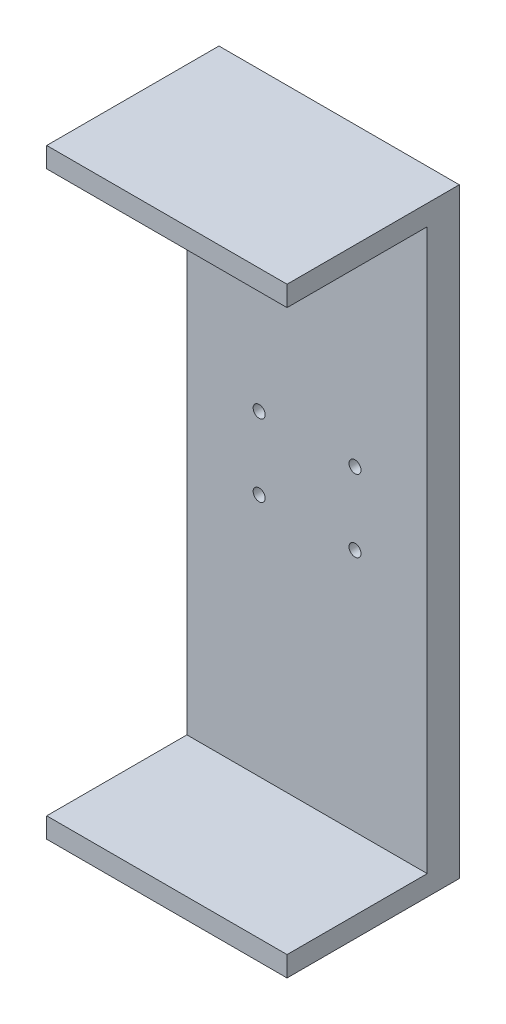
SolidWorks part; units mm, degrees
ref_plane "Front Plane" through (0, 0, 0) normal (0, 0, 1) x (1, 0, 0)
ref_plane "Top Plane" through (0, 0, 0) normal (0, 1, 0) x (1, 0, 0)
ref_plane "Right Plane" through (0, 0, 0) normal (1, 0, 0) x (0, 0, -1)
sketch "Sketch2" plane through (0, 0, 0) normal (0, 0, 1) x (1, 0, 0)
  line L6 (-13.365, 90) -> (46.635, 90)
  line L7 (-13.365, 90) -> (-13.365, -60)
  line L8 (-13.365, -60) -> (46.635, -60)
  line L9 (46.635, 90) -> (46.635, -60)
  line L10 (-13.365, 90) -> (46.635, -60) construction
  line L11 (-13.365, -60) -> (46.635, 90) construction
  circle A0 centre (28.6, 24.0168) radius 1.5
  circle A1 centre (28.6, 5.9832) radius 1.5
  circle A2 centre (4.67, 5.9832) radius 1.5
  circle A3 centre (4.67, 24.0168) radius 1.5
  point P5 (16.635, 15)
  dimension "D3" = 60
extrude "Boss-Extrude1" add sketch "Sketch2" along normal blind 8
sketch "Sketch5" plane through (0, 0, 8) normal (0, 0, 1) x (1, 0, 0)
  line L6 (46.635, 90) -> (-13.365, 90)
  line L7 (-13.365, 90) -> (-13.365, 84.9336)
  line L8 (-13.365, 90) -> (-13.365, -60) construction
  line L9 (-13.365, 84.9336) -> (46.635, 84.9336)
  line L10 (46.635, -60) -> (46.635, 90) construction
  line L11 (46.635, 84.9336) -> (46.635, 90)
  line L15 (-13.365, -54.9336) -> (46.635, -54.9336)
  line L16 (-13.365, -60) -> (-13.365, -54.9336)
  line L17 (46.635, -60) -> (-13.365, -60)
  line L18 (46.635, -54.9336) -> (46.635, -60)
extrude "Boss-Extrude2" add sketch "Sketch5" along normal blind 35
